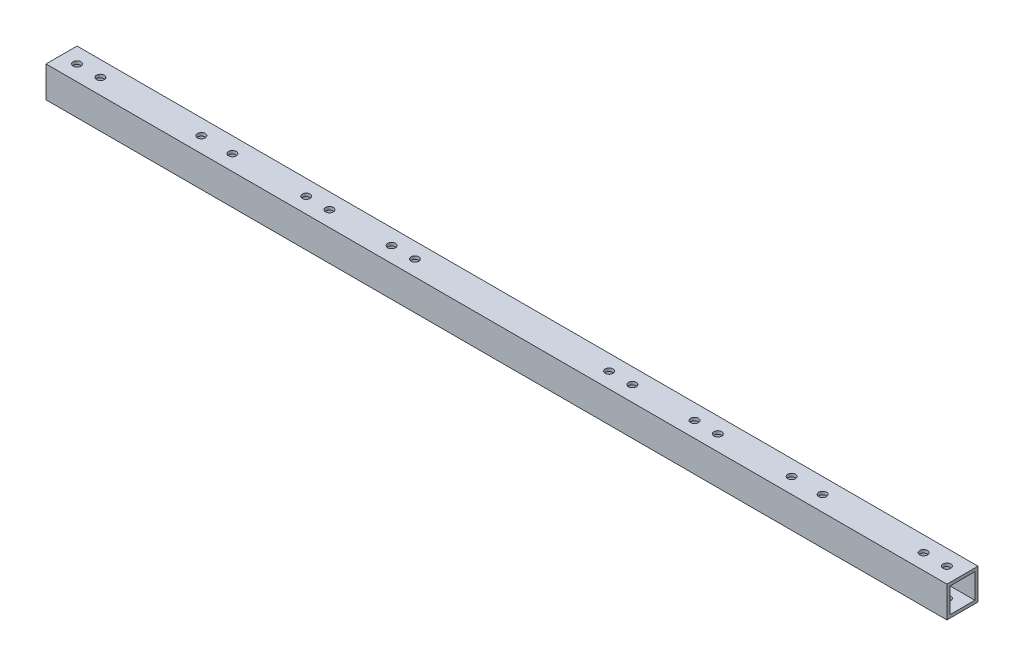
SolidWorks part; units mm, degrees
material "1345 Alloy"
ref_plane "Front Plane" through (0, 0, 0) normal (0, 0, 1) x (1, 0, 0)
ref_plane "Top Plane" through (0, 0, 0) normal (0, 1, 0) x (1, 0, 0)
ref_plane "Right Plane" through (0, 0, 0) normal (1, 0, 0) x (0, 0, -1)
sketch "Sketch1" plane through (0, 0, 0) normal (1, 0, 0) x (0, 0, -1)
  line L1 (-10, 10) -> (10, 10)
  line L2 (-10, 10) -> (-10, -10)
  line L3 (-10, -10) -> (10, -10)
  line L4 (10, 10) -> (10, -10)
  line L5 (-10, 10) -> (10, -10) construction
  line L6 (-10, -10) -> (10, 10) construction
  line L7 (-8, 8) -> (8, 8)
  line L8 (-8, 8) -> (-8, -8)
  line L9 (-8, -8) -> (8, -8)
  line L10 (8, 8) -> (8, -8)
  line L11 (-8, 8) -> (8, -8) construction
  line L12 (-8, -8) -> (8, 8) construction
  point P0 (0, 0)
  point P6 (0, 0)
  dimension "D1" = 20
  dimension "D2" = 20
  dimension "D3" = 16
  dimension "D4" = 16
extrude "Boss-Extrude1" add sketch "Sketch1" along normal blind 580
sketch "Sketch2" plane through (0, 10, 0) normal (0, 1, 0) x (1, 0, 0)
  line L0 (-16.9319, 0) -> (495.2657, 0) construction
  line L1 (580, 10) -> (580, -10) construction
  line L2 (0, 10) -> (0, -10) construction
  line L3 (10, 31.8777) -> (10, -17.8515) construction
  line L4 (570, 25.7534) -> (570, -31.8149) construction
  circle A0 centre (10, 0) radius 2.5
  circle A1 centre (570, 0) radius 2.5
  circle A3 centre (25, 0) radius 2.5
  circle A4 centre (555, 0) radius 2.5
  dimension "D1" = 5
  dimension "D2" = 5
  dimension "D7" = 15
  dimension "D3" = 10
  dimension "D4" = 10
  dimension "D8" = 15
  dimension "D5" = 2
  dimension "D6" = 2
extrude "Cut-Extrude1" cut sketch "Sketch2" against normal through all
sketch "Sketch3" plane through (0, 10, 0) normal (0, 1, 0) x (1, 0, 0)
  line L0 (-18.446, 0) -> (591.1979, 0) construction
  line L1 (0, 10) -> (0, -10) construction
  line L2 (290, 10) -> (290, -84.2137) construction
  line L3 (580, 10) -> (0, 10) construction
  circle A0 centre (110, 0) radius 2.5
  circle A1 centre (90, 0) radius 2.5
  circle A2 centre (490, 0) radius 2.5
  circle A3 centre (470, 0) radius 2.5
  dimension "D1" = 5
  dimension "D2" = 5
  dimension "D3" = 20
  dimension "D4" = 110
extrude "Cut-Extrude2" cut sketch "Sketch3" against normal through all
sketch "Sketch4" plane through (0, 10, 0) normal (0, 1, 0) x (1, 0, 0)
  line L0 (-24.4861, 0) -> (602.4727, 0) construction
  line L1 (0, 47.7165) -> (0, -47.7165) construction
  line L2 (192.5, 47.7165) -> (192.5, -47.7165) construction
  line L3 (290, 10) -> (290, -10) construction
  line L4 (580, 10) -> (0, 10) construction
  line L5 (580, -10) -> (0, -10) construction
  circle A0 centre (157.5, 0) radius 2.5
  circle A1 centre (172.5, 0) radius 2.5
  circle A2 centre (212.5, 0) radius 2.5
  circle A3 centre (227.5, 0) radius 2.5
  circle A4 centre (352.5, 0) radius 2.5
  circle A5 centre (367.5, 0) radius 2.5
  circle A6 centre (407.5, 0) radius 2.5
  circle A7 centre (422.5, 0) radius 2.5
  dimension "D2" = 5
  dimension "D3" = 5
  dimension "D4" = 20
  dimension "D5" = 15
  dimension "D1" = 192.5
extrude "Cut-Extrude3" cut sketch "Sketch4" against normal through all
